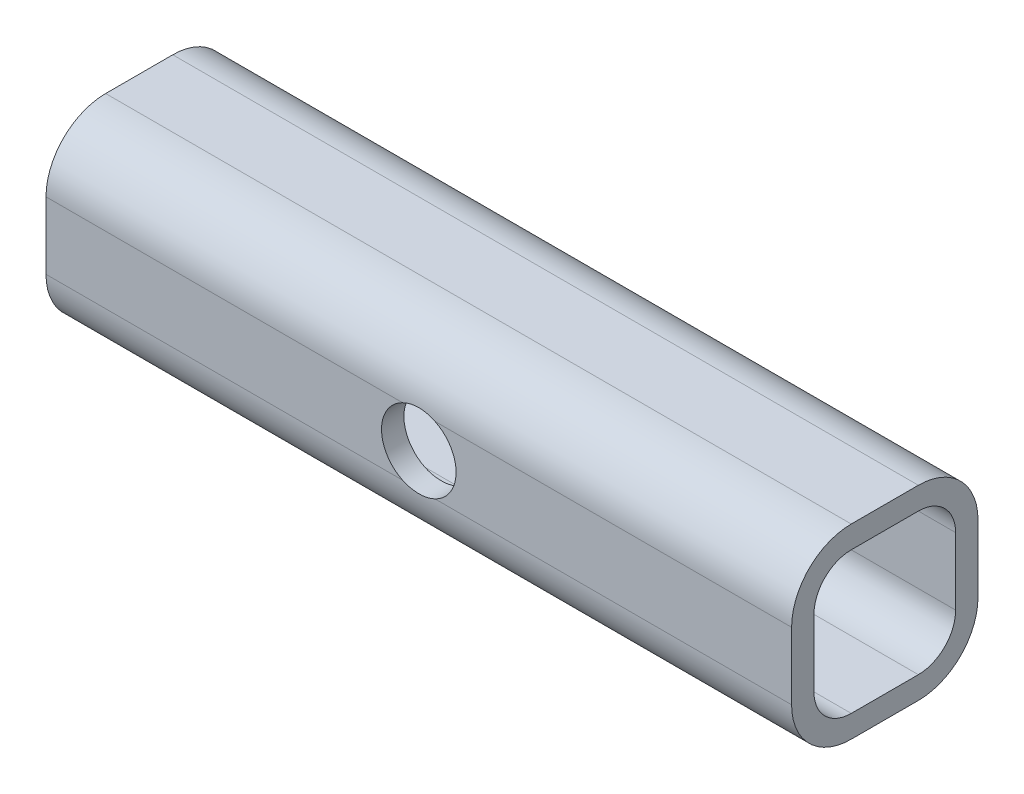
SolidWorks part; units mm, degrees
material "5052-H38, Rod (SS)"
ref_plane "Front Plane" through (0, 0, 0) normal (0, 0, 1) x (1, 0, 0)
ref_plane "Top Plane" through (0, 0, 0) normal (0, 1, 0) x (1, 0, 0)
ref_plane "Right Plane" through (0, 0, 0) normal (1, 0, 0) x (0, 0, -1)
sketch "Sketch1" plane through (0, 0, 0) normal (0, 1, 0) x (1, 0, 0)
  line L0 (0, 0) -> (-100, 0)
  dimension "D1" = 100
sketch "Sketch2" plane through (0, 0, 0) normal (1, 0, 0) x (0, 0, -1)
  line L1 (-4.5, -9.5) -> (4.5, -9.5)
  line L2 (-9.5, -4.5) -> (-9.5, 4.5)
  line L3 (-4.5, 9.5) -> (4.5, 9.5)
  line L4 (9.5, -4.5) -> (9.5, 4.5)
  line L5 (-9.5, -9.5) -> (9.5, 9.5) construction
  line L6 (-9.5, 9.5) -> (9.5, -9.5) construction
  arc A0 (-4.5, 9.5) -> (-9.5, 4.5) centre (-4.5, 4.5) ccw
  arc A1 (-9.5, -4.5) -> (-4.5, -9.5) centre (-4.5, -4.5) ccw
  arc A2 (4.5, -9.5) -> (9.5, -4.5) centre (4.5, -4.5) ccw
  arc A3 (9.5, 4.5) -> (4.5, 9.5) centre (4.5, 4.5) ccw
  point P0 (0, 0)
  dimension "D3" = 5
  dimension "D1" = 19
  dimension "D2" = 19
sweep "Sweep-Thin1" add profiles "Sketch2" path "Sketch1" parameters "D1"=3
sketch "Sketch3" plane through (0, 0, 0) normal (0, 0, 1) x (1, 0, 0)
  line L0 (0, 0) -> (-100, 0) construction
  circle A0 centre (-50, 0) radius 5
  dimension "D1" = 50
extrude "Cut-Extrude1" cut sketch "Sketch3" against normal through all both and the other way through all
